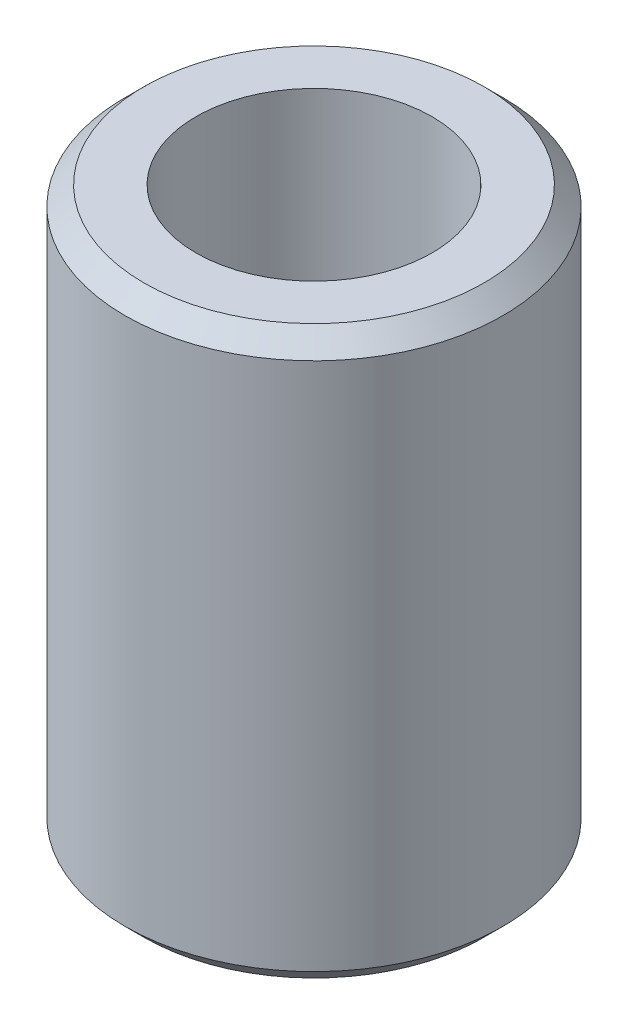
SolidWorks part; units mm, degrees
ref_plane "Front Plane" through (0, 0, 0) normal (0, 0, 1) x (1, 0, 0)
ref_plane "Top Plane" through (0, 0, 0) normal (0, 1, 0) x (1, 0, 0)
ref_plane "Right Plane" through (0, 0, 0) normal (1, 0, 0) x (0, 0, -1)
sketch "Sketch1" plane through (0, 0, 0) normal (0, 1, 0) x (1, 0, 0)
  circle A0 centre (0, 0) radius 20
  circle A1 centre (0, 0) radius 12.5
  dimension "D1" = 40
  dimension "D2" = 25
extrude "Boss-Extrude1" add sketch "Sketch1" along normal blind 60
chamfer "Chamfer1" distance 2 angle 45 2 edges at (0, 60, 20) (0, 0, 20)
